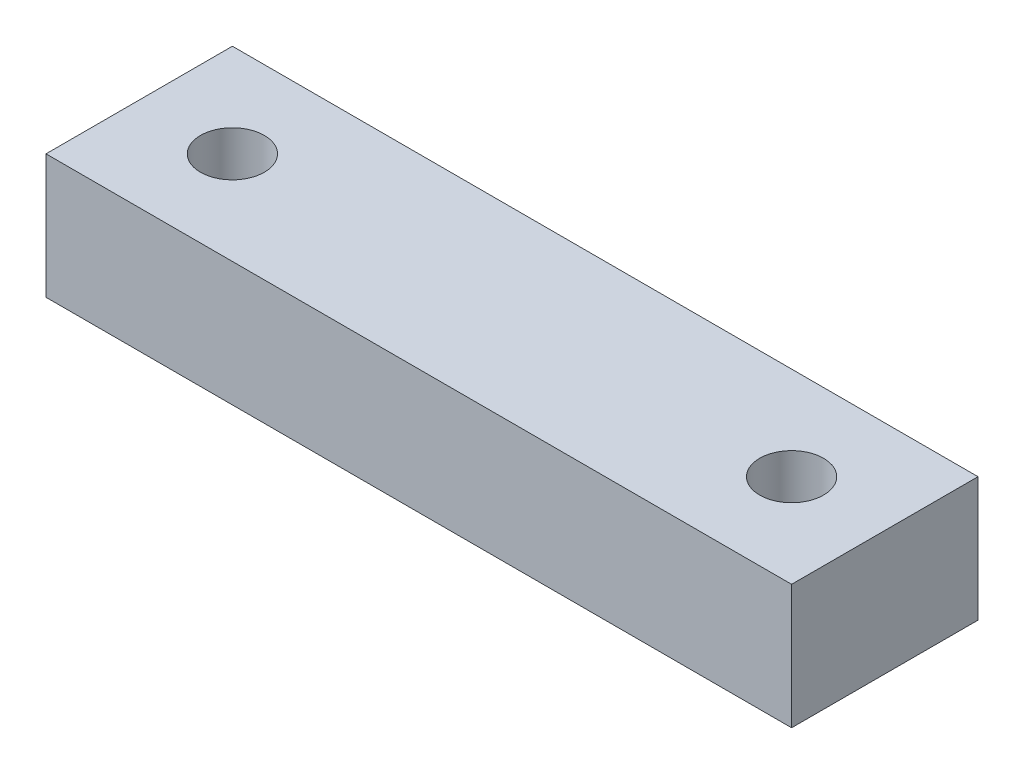
SolidWorks part; units mm, degrees
material "Beech"
ref_plane "Front Plane" through (0, 0, 0) normal (0, 0, 1) x (1, 0, 0)
ref_plane "Top Plane" through (0, 0, 0) normal (0, 1, 0) x (1, 0, 0)
ref_plane "Right Plane" through (0, 0, 0) normal (1, 0, 0) x (0, 0, -1)
sketch "Sketch1" plane through (0, 0, 0) normal (0, 1, 0) x (1, 0, 0)
  line L1 (-19.05, -4.7625) -> (19.05, -4.7625)
  line L2 (-19.05, -4.7625) -> (-19.05, 4.7625)
  line L3 (-19.05, 4.7625) -> (19.05, 4.7625)
  line L4 (19.05, -4.7625) -> (19.05, 4.7625)
  line L5 (-19.05, -4.7625) -> (19.05, 4.7625) construction
  line L6 (-19.05, 4.7625) -> (19.05, -4.7625) construction
  point P0 (0, 0)
  dimension "D1" = 38.1
  dimension "D2" = 9.525
extrude "Boss-Extrude1" add sketch "Sketch1" along normal blind 6.35
hole_wizard "#4 Clearance Hole1" positions "Sketch3" profile "Sketch2" hole size "#4" standard "ANSI Inch" end condition up to next
sketch "Sketch3" plane through (0, 6.35, 0) normal (0, 1, 0) x (1, 0, 0)
  line L0 (-19.05, 4.7625) -> (-19.05, -4.7625) construction
  point P0 (-14.2875, 0)
  point P3 (-19.05, 0)
  dimension "D1" = 4.7625
sketch "Sketch2" plane through (-14.2875, 6.35, 0) normal (1, 0, 0) x (0, 0, 1)
  line L0 (0, 0) -> (0, 6.351)
  line L1 (0, 6.351) -> (1.6319, 6.351)
  line L2 (1.6319, 6.351) -> (1.6319, 0)
  line L5 (1.6319, 0) -> (0, 0)
  line L11 (0, -6.35) -> (0, 107.95) construction
  dimension "Thru Hole Dia." = 3.2639
  dimension "Thru Hole Depth" = 6.351
mirror "Mirror1" about plane through (0, 0, 0) normal (1, 0, 0) of "#4 Clearance Hole1"
